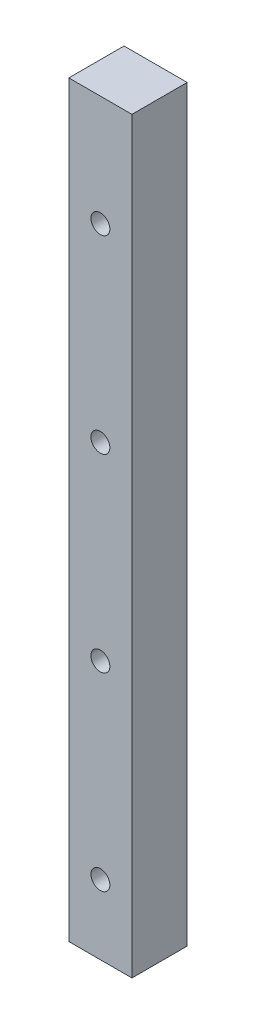
SolidWorks part; units mm, degrees
material "合金钢"
ref_plane "前视基准面" through (0, 0, 0) normal (0, 0, 1) x (1, 0, 0)
ref_plane "上视基准面" through (0, 0, 0) normal (0, 1, 0) x (1, 0, 0)
ref_plane "右视基准面" through (0, 0, 0) normal (1, 0, 0) x (0, 0, -1)
sketch "草图1" plane through (0, 0, 0) normal (0, 1, 0) x (1, 0, 0)
  line L1 (-10, 17.5) -> (10, 17.5)
  line L2 (-10, 17.5) -> (-10, 0)
  line L3 (-10, 0) -> (10, 0)
  line L4 (10, 17.5) -> (10, 0)
  point P4 (0, 0)
  dimension "D1" = 20
  dimension "D2" = 17.5
extrude "凸台-拉伸1" add sketch "草图1" along normal blind 237
sketch "草图2" plane through (0, 0, 0) normal (0, 0, 1) x (1, 0, 0)
  line L0 (-10, 0) -> (10, 0) construction
  circle A0 centre (0, 22) radius 3
  circle A5 centre (0, 82) radius 3
  circle A6 centre (0, 142) radius 3
  circle A7 centre (0, 202) radius 3
  circle A8 centre (0, 262) radius 3
  dimension "D1" = 6
  dimension "D2" = 22
  dimension "D3" = 5
extrude "切除-拉伸1" cut sketch "草图2" against normal through all
sketch "草图3" plane through (0, 0, 0) normal (0, 0, 1) x (1, 0, 0)
  circle A0 centre (0, 22) radius 4.75
  circle A1 centre (0, 82) radius 4.75
  circle A2 centre (0, 142) radius 4.75
  circle A3 centre (0, 202) radius 4.75
  circle A4 centre (0, 262) radius 4.75
  dimension "D1" = 9.5
extrude "切除-拉伸2" cut sketch "草图3" along normal blind 8.5 from surface at -17.5 starting at face at (3, 22, -17.5)
